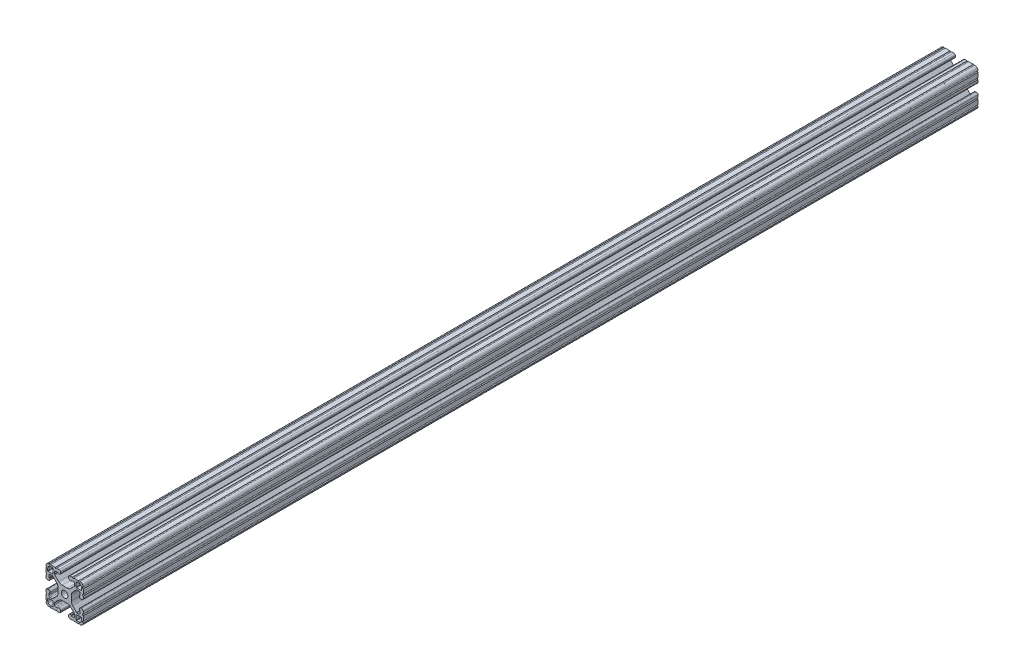
SolidWorks part; units mm, degrees
material "6061 Alloy"
ref_plane "Front Plane" through (0, 0, 0) normal (0, 0, 1) x (1, 0, 0)
ref_plane "Top Plane" through (0, 0, 0) normal (0, 1, 0) x (1, 0, 0)
ref_plane "Right Plane" through (0, 0, 0) normal (1, 0, 0) x (0, 0, -1)
sketch "Sketch1" plane through (0, 0, 0) normal (0, 0, 1) x (1, 0, 0)
  line L0 (0, 21.507) -> (0, -20.9529) construction
  line L1 (20.4424, 0) -> (-20.8151, 0) construction
  line L2 (10.0267, -12.1519) -> (6.0215, -8.1473)
  line L3 (-10.0267, 12.1519) -> (-6.0215, 8.1473)
  line L4 (-10.287, 14.5547) -> (-10.287, 12.7802)
  line L5 (-6.8141, 15.8247) -> (-9.017, 15.8247)
  line L6 (10.287, -14.5547) -> (10.287, -12.7802)
  line L7 (-6.8141, 14.986) -> (-6.8141, 15.8247)
  line L8 (6.8141, -15.8247) -> (9.017, -15.8247)
  line L9 (-2.6631, -6.7564) -> (2.6631, -6.7564)
  line L10 (6.8141, -14.986) -> (6.8141, -15.8247)
  line L11 (5.6388, -14.986) -> (6.8141, -14.986)
  line L12 (4.064, -17.4752) -> (4.064, -16.5608)
  line L13 (7.9756, -19.05) -> (5.6388, -19.05)
  line L14 (14.3256, -19.05) -> (9.4996, -19.05)
  line L15 (15.875, -19.05) -> (15.8496, -19.05)
  line L16 (19.05, -15.8496) -> (19.05, -15.875)
  line L17 (19.05, -9.4996) -> (19.05, -14.3256)
  line L18 (19.05, -5.6388) -> (19.05, -7.9756)
  line L19 (-5.6388, 14.986) -> (-6.8141, 14.986)
  line L20 (-4.064, 17.4752) -> (-4.064, 16.5608)
  line L21 (-7.9756, 19.05) -> (-5.6388, 19.05)
  line L22 (16.5608, -4.064) -> (17.4752, -4.064)
  line L23 (-14.3256, 19.05) -> (-9.4996, 19.05)
  line L24 (14.986, -6.7506) -> (14.986, -5.6388)
  line L25 (15.879, -6.7506) -> (14.986, -6.7506)
  line L26 (-15.875, 19.05) -> (-15.8496, 19.05)
  line L27 (-19.05, 15.8496) -> (-19.05, 15.875)
  line L28 (15.879, -8.9192) -> (15.879, -6.7506)
  line L29 (12.7428, -10.1892) -> (14.609, -10.1892)
  line L30 (-19.05, 9.4996) -> (-19.05, 14.3256)
  line L31 (-19.05, 5.6388) -> (-19.05, 7.9756)
  line L32 (8.1479, -5.9632) -> (12.1142, -9.9289)
  line L33 (16.891, -11.8618) -> (12.2428, -11.8618)
  line L34 (11.8618, -12.2428) -> (11.8618, -16.891)
  line L35 (12.2428, -17.272) -> (14.478, -17.272)
  line L36 (17.272, 14.478) -> (17.272, 12.2428)
  line L37 (12.2428, 17.272) -> (14.478, 17.272)
  line L38 (11.8618, 12.2428) -> (11.8618, 16.891)
  line L39 (16.891, 11.8618) -> (12.2428, 11.8618)
  line L40 (17.272, -14.478) -> (17.272, -12.2428)
  line L41 (-16.5608, 4.064) -> (-17.4752, 4.064)
  line L42 (-14.986, 6.7506) -> (-14.986, 5.6388)
  line L43 (-15.879, 6.7506) -> (-14.986, 6.7506)
  line L44 (-15.879, 8.9192) -> (-15.879, 6.7506)
  line L45 (-12.7428, 10.1892) -> (-14.609, 10.1892)
  line L46 (-8.1479, 5.9632) -> (-12.1142, 9.9289)
  line L47 (-6.7564, -2.6043) -> (-6.7564, 2.6043)
  line L48 (-17.272, -14.478) -> (-17.272, -12.2428)
  line L49 (-16.891, 11.8618) -> (-12.2428, 11.8618)
  line L50 (-11.8618, 12.2428) -> (-11.8618, 16.891)
  line L51 (-12.2428, 17.272) -> (-14.478, 17.272)
  line L52 (-17.272, 14.478) -> (-17.272, 12.2428)
  line L53 (-12.2428, -17.272) -> (-14.478, -17.272)
  line L54 (-11.8618, -12.2428) -> (-11.8618, -16.891)
  line L55 (-16.891, -11.8618) -> (-12.2428, -11.8618)
  line L56 (-8.1479, -5.9632) -> (-12.1142, -9.9289)
  line L57 (-12.7428, -10.1892) -> (-14.609, -10.1892)
  line L58 (-15.879, -8.9192) -> (-15.879, -6.7506)
  line L59 (-15.879, -6.7506) -> (-14.986, -6.7506)
  line L60 (-14.986, -6.7506) -> (-14.986, -5.6388)
  line L61 (-16.5608, -4.064) -> (-17.4752, -4.064)
  line L62 (-19.05, -5.6388) -> (-19.05, -7.9756)
  line L63 (-19.05, -9.4996) -> (-19.05, -14.3256)
  line L64 (-19.05, -15.8496) -> (-19.05, -15.875)
  line L65 (-15.875, -19.05) -> (-15.8496, -19.05)
  line L66 (-14.3256, -19.05) -> (-9.4996, -19.05)
  line L67 (-7.9756, -19.05) -> (-5.6388, -19.05)
  line L68 (-4.064, -17.4752) -> (-4.064, -16.5608)
  line L69 (-5.6388, -14.986) -> (-6.8141, -14.986)
  line L70 (-6.8141, -14.986) -> (-6.8141, -15.8247)
  line L71 (-6.8141, -15.8247) -> (-9.017, -15.8247)
  line L72 (-10.287, -14.5547) -> (-10.287, -12.7802)
  line L73 (-10.0267, -12.1519) -> (-6.0215, -8.1473)
  line L95 (6.7564, -2.6043) -> (6.7564, 2.6043)
  line L96 (8.1479, 5.9632) -> (12.1142, 9.9289)
  line L97 (12.7428, 10.1892) -> (14.609, 10.1892)
  line L98 (15.879, 8.9192) -> (15.879, 6.7506)
  line L99 (15.879, 6.7506) -> (14.986, 6.7506)
  line L100 (14.986, 6.7506) -> (14.986, 5.6388)
  line L101 (16.5608, 4.064) -> (17.4752, 4.064)
  line L102 (19.05, 5.6388) -> (19.05, 7.9756)
  line L103 (19.05, 9.4996) -> (19.05, 14.3256)
  line L104 (19.05, 15.8496) -> (19.05, 15.875)
  line L105 (15.875, 19.05) -> (15.8496, 19.05)
  line L106 (14.3256, 19.05) -> (9.4996, 19.05)
  line L107 (7.9756, 19.05) -> (5.6388, 19.05)
  line L108 (4.064, 17.4752) -> (4.064, 16.5608)
  line L109 (5.6388, 14.986) -> (6.8141, 14.986)
  line L110 (6.8141, 14.986) -> (6.8141, 15.8247)
  line L111 (6.8141, 15.8247) -> (9.017, 15.8247)
  line L112 (10.287, 14.5547) -> (10.287, 12.7802)
  line L113 (10.0267, 12.1519) -> (6.0215, 8.1473)
  line L114 (2.6631, 6.7564) -> (-2.6631, 6.7564)
  arc A0 (10.0267, -12.1519) -> (10.287, -12.7802) centre (9.3985, -12.7802) cw
  arc A1 (10.287, -14.5547) -> (9.017, -15.8247) centre (9.017, -14.5547) cw
  arc A2 (4.064, -16.5608) -> (5.6388, -14.986) centre (5.6388, -16.5608) cw
  arc A3 (-10.0267, 12.1519) -> (-10.287, 12.7802) centre (-9.3985, 12.7802) cw
  arc A4 (-10.287, 14.5547) -> (-9.017, 15.8247) centre (-9.017, 14.5547) cw
  arc A5 (5.6388, -19.05) -> (4.064, -17.4752) centre (5.6388, -17.4752) cw
  arc A6 (7.9756, -19.05) -> (9.4996, -19.05) centre (8.7376, -19.05) cw
  arc A7 (-4.064, 16.5608) -> (-5.6388, 14.986) centre (-5.6388, 16.5608) cw
  arc A8 (14.3256, -19.05) -> (15.8496, -19.05) centre (15.0876, -19.05) cw
  arc A9 (19.05, -15.875) -> (15.875, -19.05) centre (15.875, -15.875) cw
  arc A10 (6.0215, -8.1473) -> (2.6631, -6.7564) centre (2.6631, -11.5062) ccw
  arc A11 (-6.0215, -8.1473) -> (-2.6631, -6.7564) centre (-2.6631, -11.5062) cw
  arc A12 (19.05, -15.8496) -> (19.05, -14.3256) centre (19.05, -15.0876) cw
  arc A13 (19.05, -9.4996) -> (19.05, -7.9756) centre (19.05, -8.7376) cw
  arc A14 (17.4752, -4.064) -> (19.05, -5.6388) centre (17.4752, -5.6388) cw
  arc A15 (14.986, -5.6388) -> (16.5608, -4.064) centre (16.5608, -5.6388) cw
  arc A16 (15.879, -8.9192) -> (14.609, -10.1892) centre (14.609, -8.9192) cw
  arc A17 (12.7428, -10.1892) -> (12.1142, -9.9289) centre (12.7428, -9.3002) cw
  arc A18 (16.891, -11.8618) -> (17.272, -12.2428) centre (16.891, -12.2428) cw
  arc A19 (-5.6388, 19.05) -> (-4.064, 17.4752) centre (-5.6388, 17.4752) cw
  arc A20 (-7.9756, 19.05) -> (-9.4996, 19.05) centre (-8.7376, 19.05) cw
  arc A21 (-14.3256, 19.05) -> (-15.8496, 19.05) centre (-15.0876, 19.05) cw
  arc A22 (11.8618, -12.2428) -> (12.2428, -11.8618) centre (12.2428, -12.2428) cw
  arc A23 (-19.05, 15.875) -> (-15.875, 19.05) centre (-15.875, 15.875) cw
  arc A24 (12.2428, -17.272) -> (11.8618, -16.891) centre (12.2428, -16.891) cw
  arc A25 (17.272, -14.478) -> (14.478, -17.272) centre (14.478, -14.478) cw
  arc A26 (-19.05, 15.8496) -> (-19.05, 14.3256) centre (-19.05, 15.0876) cw
  arc A27 (-19.05, 9.4996) -> (-19.05, 7.9756) centre (-19.05, 8.7376) cw
  arc A28 (-17.4752, 4.064) -> (-19.05, 5.6388) centre (-17.4752, 5.6388) cw
  arc A29 (-14.986, 5.6388) -> (-16.5608, 4.064) centre (-16.5608, 5.6388) cw
  arc A30 (-15.879, 8.9192) -> (-14.609, 10.1892) centre (-14.609, 8.9192) cw
  arc A31 (-12.7428, 10.1892) -> (-12.1142, 9.9289) centre (-12.7428, 9.3002) cw
  arc A32 (-8.1479, 5.9632) -> (-6.7564, 2.6043) centre (-11.5062, 2.6043) cw
  arc A33 (-6.7564, -2.6043) -> (-8.1479, -5.9632) centre (-11.5062, -2.6043) cw
  arc A34 (-16.891, 11.8618) -> (-17.272, 12.2428) centre (-16.891, 12.2428) cw
  arc A35 (-11.8618, 12.2428) -> (-12.2428, 11.8618) centre (-12.2428, 12.2428) cw
  arc A36 (17.272, 14.478) -> (14.478, 17.272) centre (14.478, 14.478) ccw
  arc A37 (12.2428, 17.272) -> (11.8618, 16.891) centre (12.2428, 16.891) ccw
  arc A38 (11.8618, 12.2428) -> (12.2428, 11.8618) centre (12.2428, 12.2428) ccw
  arc A39 (16.891, 11.8618) -> (17.272, 12.2428) centre (16.891, 12.2428) ccw
  arc A40 (-12.2428, 17.272) -> (-11.8618, 16.891) centre (-12.2428, 16.891) cw
  circle A41 centre (0, 0) radius 3.3274
  arc A42 (-17.272, 14.478) -> (-14.478, 17.272) centre (-14.478, 14.478) cw
  arc A43 (-17.272, -14.478) -> (-14.478, -17.272) centre (-14.478, -14.478) ccw
  arc A44 (-12.2428, -17.272) -> (-11.8618, -16.891) centre (-12.2428, -16.891) ccw
  arc A45 (-11.8618, -12.2428) -> (-12.2428, -11.8618) centre (-12.2428, -12.2428) ccw
  arc A46 (-16.891, -11.8618) -> (-17.272, -12.2428) centre (-16.891, -12.2428) ccw
  arc A47 (-12.7428, -10.1892) -> (-12.1142, -9.9289) centre (-12.7428, -9.3002) ccw
  arc A48 (-15.879, -8.9192) -> (-14.609, -10.1892) centre (-14.609, -8.9192) ccw
  arc A49 (-14.986, -5.6388) -> (-16.5608, -4.064) centre (-16.5608, -5.6388) ccw
  arc A50 (-17.4752, -4.064) -> (-19.05, -5.6388) centre (-17.4752, -5.6388) ccw
  arc A51 (-19.05, -9.4996) -> (-19.05, -7.9756) centre (-19.05, -8.7376) ccw
  arc A52 (-19.05, -15.8496) -> (-19.05, -14.3256) centre (-19.05, -15.0876) ccw
  arc A53 (-19.05, -15.875) -> (-15.875, -19.05) centre (-15.875, -15.875) ccw
  arc A54 (-14.3256, -19.05) -> (-15.8496, -19.05) centre (-15.0876, -19.05) ccw
  arc A55 (-7.9756, -19.05) -> (-9.4996, -19.05) centre (-8.7376, -19.05) ccw
  arc A56 (-5.6388, -19.05) -> (-4.064, -17.4752) centre (-5.6388, -17.4752) ccw
  arc A57 (-4.064, -16.5608) -> (-5.6388, -14.986) centre (-5.6388, -16.5608) ccw
  arc A58 (-10.287, -14.5547) -> (-9.017, -15.8247) centre (-9.017, -14.5547) ccw
  arc A59 (-10.0267, -12.1519) -> (-10.287, -12.7802) centre (-9.3985, -12.7802) ccw
  arc A86 (6.7564, -2.6043) -> (8.1479, -5.9632) centre (11.5062, -2.6043) ccw
  arc A87 (8.1479, 5.9632) -> (6.7564, 2.6043) centre (11.5062, 2.6043) ccw
  arc A88 (12.7428, 10.1892) -> (12.1142, 9.9289) centre (12.7428, 9.3002) ccw
  arc A89 (15.879, 8.9192) -> (14.609, 10.1892) centre (14.609, 8.9192) ccw
  arc A90 (14.986, 5.6388) -> (16.5608, 4.064) centre (16.5608, 5.6388) ccw
  arc A91 (17.4752, 4.064) -> (19.05, 5.6388) centre (17.4752, 5.6388) ccw
  arc A92 (19.05, 9.4996) -> (19.05, 7.9756) centre (19.05, 8.7376) ccw
  arc A93 (19.05, 15.8496) -> (19.05, 14.3256) centre (19.05, 15.0876) ccw
  arc A94 (19.05, 15.875) -> (15.875, 19.05) centre (15.875, 15.875) ccw
  arc A95 (14.3256, 19.05) -> (15.8496, 19.05) centre (15.0876, 19.05) ccw
  arc A96 (7.9756, 19.05) -> (9.4996, 19.05) centre (8.7376, 19.05) ccw
  arc A97 (5.6388, 19.05) -> (4.064, 17.4752) centre (5.6388, 17.4752) ccw
  arc A98 (4.064, 16.5608) -> (5.6388, 14.986) centre (5.6388, 16.5608) ccw
  arc A99 (10.287, 14.5547) -> (9.017, 15.8247) centre (9.017, 14.5547) ccw
  arc A100 (10.0267, 12.1519) -> (10.287, 12.7802) centre (9.3985, 12.7802) ccw
  arc A101 (2.6631, 6.7564) -> (6.0215, 8.1473) centre (2.6631, 11.5062) ccw
  arc A102 (-6.0215, 8.1473) -> (-2.6631, 6.7564) centre (-2.6631, 11.5062) ccw
  dimension "D1" = 6.6548
  dimension "D2" = 38.1
  dimension "D3" = 20.574
  dimension "D4" = 12.2936
  dimension "D5" = 19.05
  dimension "D6" = 8.128
  dimension "D7" = 3.048
  dimension "D8" = 4.064
  dimension "D9" = 13.5128
extrude "Extrude1" add sketch "Sketch1" against normal blind 914.4
